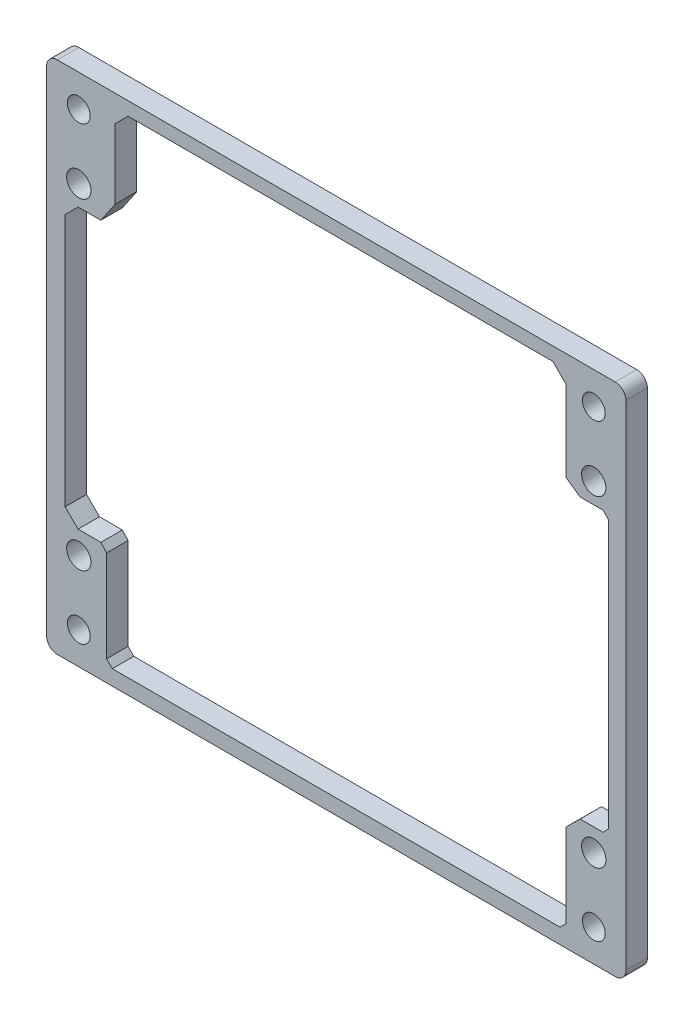
SolidWorks part; units mm, degrees
ref_plane "Alzado" through (0, 0, 0) normal (0, 0, 1) x (1, 0, 0)
ref_plane "Planta" through (0, 0, 0) normal (0, 1, 0) x (1, 0, 0)
ref_plane "Vista lateral" through (0, 0, 0) normal (1, 0, 0) x (0, 0, -1)
sketch "Model" plane through (0, 0, 0) normal (0, 0, 1) x (1, 0, 0)
  line L0 (71.6513, -46.9351) -> (131.056, -46.9351)
  line L1 (69.4513, -114.9375) -> (132.056, -114.9375)
  line L2 (62.8513, -63.2351) -> (62.8513, -98.6375)
  line L3 (138.856, -62.2351) -> (138.856, -99.6375)
  line L4 (64.6513, -61.4351) -> (67.8513, -61.4351)
  line L5 (69.8513, -58.4981) -> (69.8513, -48.7351)
  line L6 (68.6513, -114.1375) -> (68.6513, -101.3175)
  line L7 (67.8513, -100.4375) -> (64.6513, -100.4375)
  line L8 (138.056, -100.4375) -> (134.856, -100.4375)
  line L9 (132.856, -102.4214) -> (132.856, -114.1375)
  line L10 (134.856, -61.4351) -> (138.056, -61.4351)
  line L11 (132.856, -48.7351) -> (132.856, -60.0487)
  line L12 (67.8513, -61.4351) -> (69.8513, -58.4981)
  line L13 (134.856, -61.4351) -> (132.856, -60.0487)
  line L14 (134.856, -100.4375) -> (132.856, -102.4214)
  line L15 (67.8513, -100.4375) -> (68.6513, -101.3175)
  line L16 (68.6513, -114.1375) -> (69.4513, -114.9375)
  line L17 (64.6513, -100.4375) -> (62.8513, -98.6375)
  line L18 (64.6513, -61.4351) -> (62.8513, -63.2351)
  line L19 (71.6513, -46.9351) -> (69.8513, -48.7351)
  line L20 (131.056, -46.9351) -> (132.856, -48.7351)
  line L21 (132.056, -114.9375) -> (132.856, -114.1375)
  line L22 (138.056, -100.4375) -> (138.856, -99.6375)
  line L23 (138.056, -61.4351) -> (138.856, -62.2351)
  line L24 (60.2635, -46.5549) -> (60.2635, -115.5573)
  line L25 (139.7682, -45.0549) -> (61.7635, -45.0549)
  line L26 (141.2682, -115.5573) -> (141.2682, -46.5549)
  line L27 (61.7635, -117.0573) -> (139.7682, -117.0573)
  circle A0 centre (136.7685, -103.558) radius 1.7
  circle A1 centre (136.7685, -58.5546) radius 1.7
  circle A2 centre (136.7685, -112.5577) radius 1.6003
  circle A3 centre (136.7685, -49.5549) radius 1.6003
  circle A4 centre (64.7635, -103.558) radius 1.7
  circle A5 centre (64.7635, -58.5546) radius 1.7
  circle A6 centre (64.7635, -49.5549) radius 1.6003
  circle A7 centre (64.7635, -112.5577) radius 1.6003
  arc A8 (60.2635, -115.5573) -> (61.7635, -117.0573) centre (61.7635, -115.5573) ccw
  arc A9 (139.7682, -117.0573) -> (141.2682, -115.5573) centre (139.7682, -115.5573) ccw
  arc A10 (141.2682, -46.5549) -> (139.7682, -45.0549) centre (139.7682, -46.5549) ccw
  arc A11 (61.7635, -45.0549) -> (60.2635, -46.5549) centre (61.7635, -46.5549) ccw
extrude "Saliente-Extruir1" add sketch "Model" along normal blind 3
